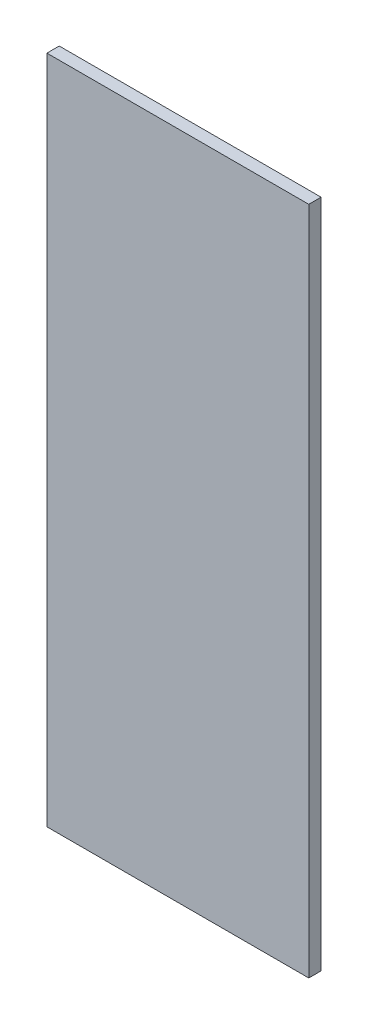
SolidWorks part; units mm, degrees
ref_plane "Front Plane" through (0, 0, 0) normal (0, 0, 1) x (1, 0, 0)
ref_plane "Top Plane" through (0, 0, 0) normal (0, 1, 0) x (1, 0, 0)
ref_plane "Right Plane" through (0, 0, 0) normal (1, 0, 0) x (0, 0, -1)
sketch "Sketch1" plane through (0, 0, 0) normal (0, 0, 1) x (1, 0, 0)
  line L1 (0, 0) -> (34, 0)
  line L2 (0, 0) -> (0, -87)
  line L3 (0, -87) -> (34, -87)
  line L4 (34, 0) -> (34, -87)
  dimension "D1" = 87
  dimension "D2" = 34
extrude "Boss-Extrude1" add sketch "Sketch1" along normal blind 1.6
